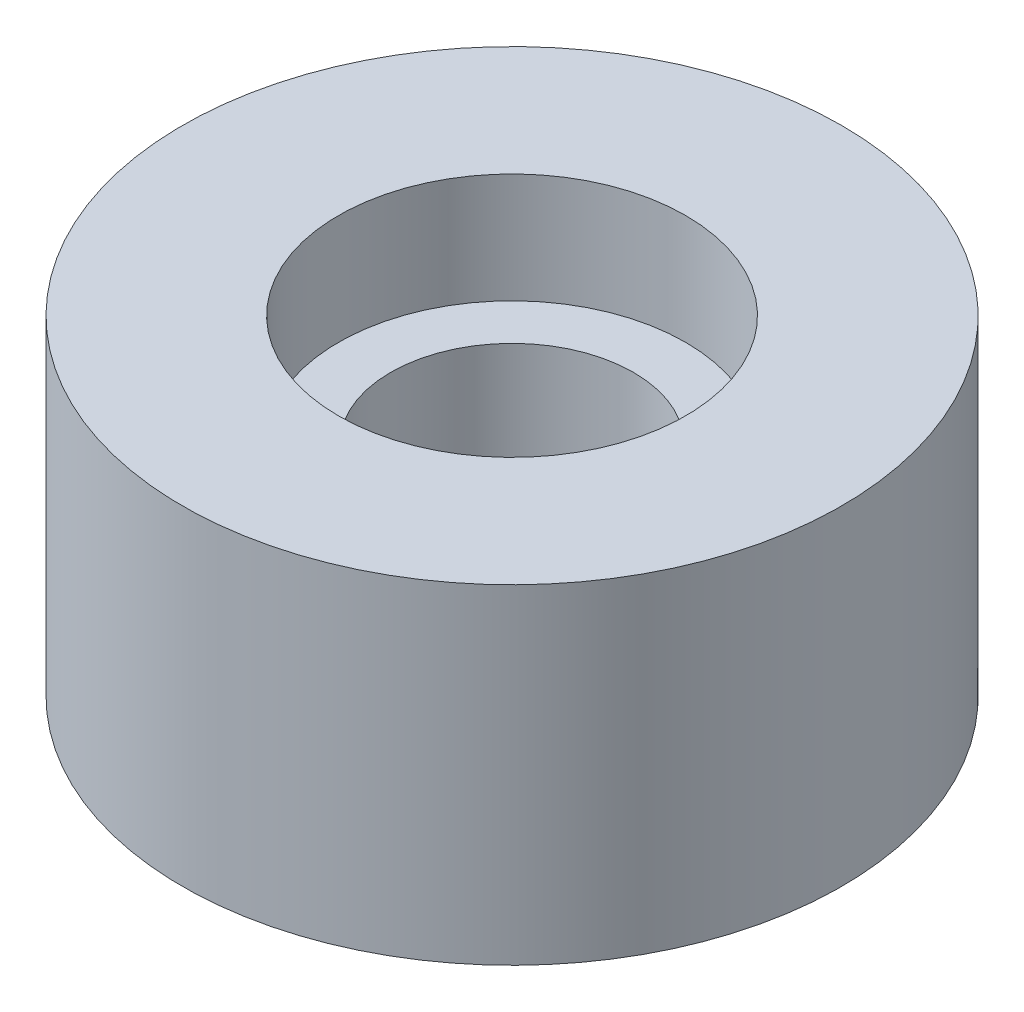
SolidWorks part; units mm, degrees
ref_plane "Front Plane" through (0, 0, 0) normal (0, 0, 1) x (1, 0, 0)
ref_plane "Top Plane" through (0, 0, 0) normal (0, 1, 0) x (1, 0, 0)
ref_plane "Right Plane" through (0, 0, 0) normal (1, 0, 0) x (0, 0, -1)
sketch "Sketch1" plane through (0, 0, 0) normal (0, 1, 0) x (1, 0, 0)
  circle A0 centre (0, 0) radius 38.1
  dimension "D1" = 76.2
extrude "Boss-Extrude1" add sketch "Sketch1" along normal blind 38.1
sketch "Sketch2" plane through (0, 0, 0) normal (0, -1, 0) x (1, 0, 0)
  circle A0 centre (0, 0) radius 14.0462
  dimension "D1" = 28.0924
extrude "Cut-Extrude1" cut sketch "Sketch2" against normal blind 76.2
sketch "Sketch3" plane through (0, 38.1, 0) normal (0, 1, 0) x (1, 0, 0)
  circle A0 centre (0, 0) radius 20.066
  dimension "D1" = 40.132
extrude "Cut-Extrude2" cut sketch "Sketch3" against normal blind 12.7
sketch "Sketch4" plane through (0, 0, 0) normal (0, -1, 0) x (1, 0, 0)
  circle A0 centre (0, 0) radius 30.0355
  dimension "D1" = 60.071
extrude "Cut-Extrude3" cut sketch "Sketch4" against normal blind 12.7
